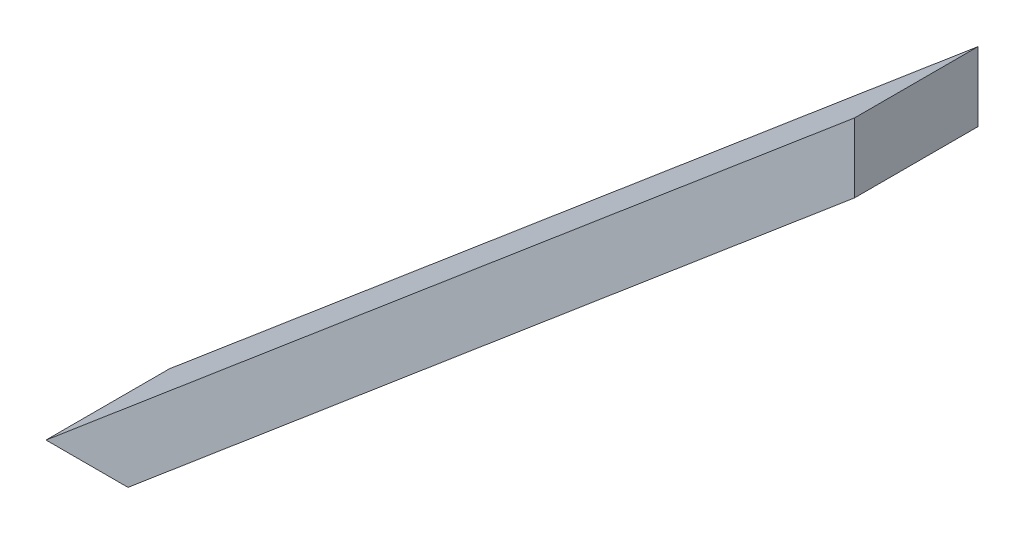
SolidWorks part; units mm, degrees
ref_plane "Front Plane" through (0, 0, 0) normal (0, 0, 1) x (1, 0, 0)
ref_plane "Top Plane" through (0, 0, 0) normal (0, 1, 0) x (1, 0, 0)
ref_plane "Right Plane" through (0, 0, 0) normal (1, 0, 0) x (0, 0, -1)
sketch "Sketch1" plane through (0, 0, 0) normal (0, 0, 1) x (1, 0, 0)
  line L0 (-414.6443, 88.9) -> (-414.6443, 39.0183)
  line L2 (-414.6443, 39.0183) -> (-937.6361, -402.9289)
  line L4 (-937.6361, -402.9289) -> (-996.6652, -402.9289)
  line L5 (-996.6652, -402.9289) -> (-414.6443, 88.9)
  line L6 (-414.6422, 88.8975) -> (31857.5983, -38101.4474) construction
  dimension "D1" = 38.1
  dimension "D2" = 762
extrude "Boss-Extrude1" add sketch "Sketch1" along normal mid plane 88.9
